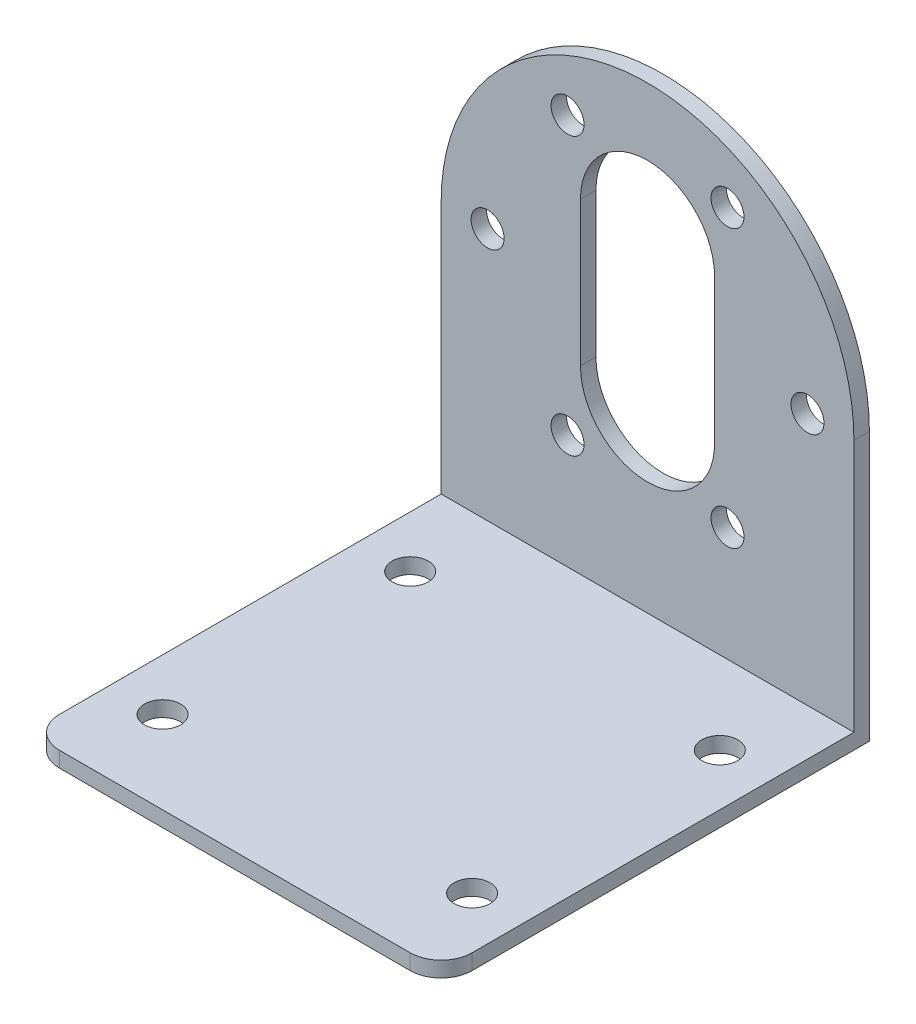
SolidWorks part; units mm, degrees
material "AISI 4340 钢，退火"
ref_plane "前视基准面" through (0, 0, 0) normal (0, 0, 1) x (1, 0, 0)
ref_plane "上视基准面" through (0, 0, 0) normal (0, 1, 0) x (1, 0, 0)
ref_plane "右视基准面" through (0, 0, 0) normal (1, 0, 0) x (0, 0, -1)
sketch "草图1" plane through (0, 0, 0) normal (0, 1, 0) x (1, 0, 0)
  line L1 (-20, 0) -> (20, 0)
  line L2 (-20, 0) -> (-20, -37)
  line L3 (-17, -40) -> (17, -40)
  line L4 (20, 0) -> (20, -37)
  circle A2 centre (-15, -32) radius 1.75
  circle A4 centre (-15, -8) radius 1.75
  circle A5 centre (15, -8) radius 1.75
  circle A6 centre (15, -32) radius 1.75
  arc A7 (17, -40) -> (20, -37) centre (17, -37) ccw
  arc A8 (-17, -40) -> (-20, -37) centre (-17, -37) cw
  point P4 (0, 0)
  point P17 (20, -40)
  dimension "D3" = 3.5
  dimension "D7" = 3
  dimension "D1" = 40
  dimension "D2" = 40
  dimension "D4" = 8
  dimension "D5" = 5
  dimension "D6" = 5
  dimension "D8" = 24
sketch "草图2" plane through (0, 0, 0) normal (0, 0, 1) x (1, 0, 0)
  line L2 (20, 0) -> (-20, 0)
  line L3 (20, 0) -> (20, 26)
  line L5 (-20, 0) -> (-20, 26)
  line L6 (-6.5, 33) -> (-6.5, 19)
  line L8 (6.5, 33) -> (6.5, 19)
  line L10 (0, 26) -> (0.4808, 26.5178) construction
  arc A0 (20, 26) -> (-20, 26) centre (0, 26) ccw
  circle A1 centre (0, 26) radius 15.5
  circle A2 centre (-15.5, 26) radius 1.6
  circle A3 centre (-7.75, 39.4234) radius 1.6
  circle A4 centre (7.75, 39.4234) radius 1.6
  circle A5 centre (15.5, 26) radius 1.6
  circle A6 centre (7.75, 12.5766) radius 1.6
  circle A7 centre (-7.75, 12.5766) radius 1.6
  arc A8 (6.5, 33) -> (-6.5, 33) centre (0, 33) ccw
  arc A9 (-6.5, 19) -> (6.5, 19) centre (0, 19) ccw
  point P21 (0, 26)
  dimension "D3" = 14
  dimension "D2" = 6
  dimension "D5" = 20
  dimension "D6" = 31
  dimension "D1" = 40
  dimension "D4" = 26
  dimension "D7" = 13
extrude "凸台-拉伸1" add sketch "草图1" along normal blind 1.5
extrude "凸台-拉伸2" add sketch "草图2" against normal blind 1.5 contours A4 | A3 | A2 | A0 L5 L2 L3 | L8 A9 L6 A8 | A5 | A7 | A6
